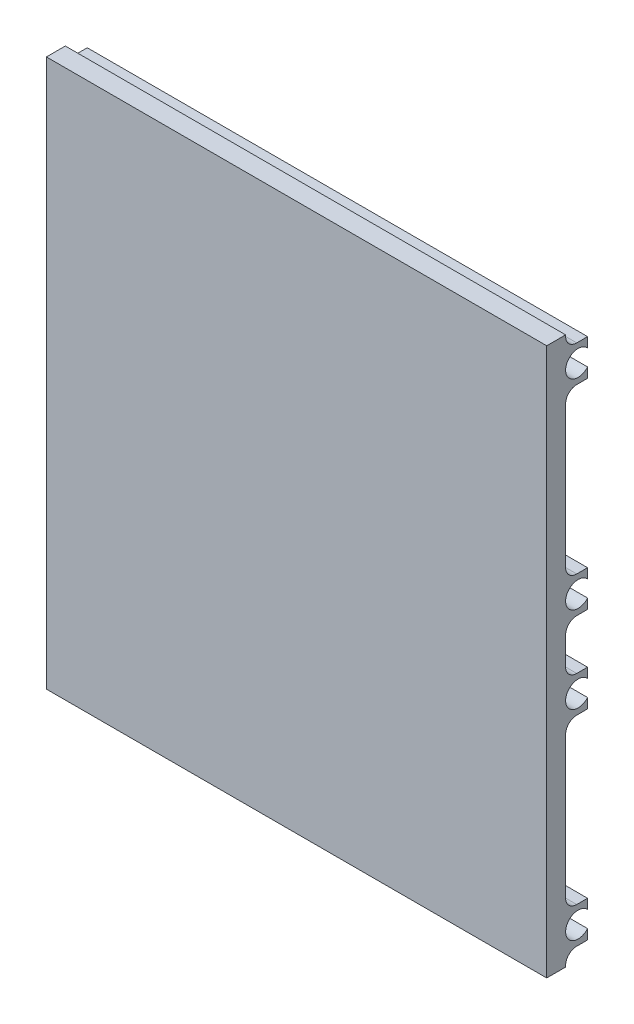
SolidWorks part; units mm, degrees
ref_plane "Спереди" through (0, 0, 0) normal (0, 0, 1) x (1, 0, 0)
ref_plane "Сверху" through (0, 0, 0) normal (0, 1, 0) x (1, 0, 0)
ref_plane "Справа" through (0, 0, 0) normal (1, 0, 0) x (0, 0, -1)
ref_plane "Плоскость4" through (90, 0, 0) normal (1, 0, 0) x (0, 0, -1)
sketch "Эскиз1" plane through (90, 0, 0) normal (1, 0, 0) x (0, 0, -1)
  line L0 (6.75, 225.9062) -> (6.75, 320.75)
  line L1 (6.75, 320.75) -> (-38.0938, 320.75)
  line L2 (-38.0938, 318.25) -> (-37.5, 318.25)
  line L3 (-37.5, 318.25) -> (-37.5, 284.75)
  line L4 (-37.5, 284.75) -> (-38.0938, 284.75)
  line L5 (-38.0938, 282.25) -> (-37.5, 282.25)
  line L6 (-37.5, 282.25) -> (-37.5, 269.25)
  line L7 (-37.5, 269.25) -> (-38.0938, 269.25)
  line L8 (-38.0938, 266.75) -> (-37.5, 266.75)
  line L9 (-37.5, 266.75) -> (-37.5, 233.25)
  line L10 (-37.5, 233.25) -> (-38.0938, 233.25)
  line L11 (-38.0938, 230.75) -> (-37.5, 230.75)
  line L12 (-37.5, 230.75) -> (-37.5, 226.5)
  line L13 (-37.5, 226.5) -> (-33.25, 226.5)
  line L14 (-33.25, 226.5) -> (-33.25, 225.9062)
  line L15 (-30.75, 225.9062) -> (-30.75, 226.5)
  line L16 (-30.75, 226.5) -> (-22.25, 226.5)
  line L17 (-22.25, 226.5) -> (-22.25, 225.9062)
  line L18 (-19.75, 225.9062) -> (-19.75, 226.5)
  line L19 (-19.75, 226.5) -> (-6.75, 226.5)
  line L20 (-6.75, 226.5) -> (-6.75, 225.9062)
  line L21 (-4.25, 225.9062) -> (-4.25, 226.5)
  line L22 (-4.25, 226.5) -> (4.25, 226.5)
  line L23 (4.25, 226.5) -> (4.25, 225.9062)
  arc A0 (-38.0938, 320.75) -> (-38.0938, 318.25) centre (-39.75, 319.5) ccw
  arc A1 (-38.0938, 284.75) -> (-38.0938, 282.25) centre (-39.75, 283.5) ccw
  arc A2 (-38.0938, 269.25) -> (-38.0938, 266.75) centre (-39.75, 268) ccw
  arc A3 (-38.0938, 233.25) -> (-38.0938, 230.75) centre (-39.75, 232) ccw
  arc A4 (-33.25, 225.9062) -> (-30.75, 225.9062) centre (-32, 224.25) ccw
  arc A5 (-22.25, 225.9062) -> (-19.75, 225.9062) centre (-21, 224.25) ccw
  arc A6 (-6.75, 225.9062) -> (-4.25, 225.9062) centre (-5.5, 224.25) ccw
  arc A7 (4.25, 225.9062) -> (6.75, 225.9062) centre (5.5, 224.25) ccw
extrude "Бобышка-Вытянуть1" add sketch "Эскиз1" against normal blind 90
sketch "Эскиз2" plane through (0, 320.75, 0) normal (0, 1, 0) x (-1, 0, 0)
  line L0 (-90, -6.75) -> (-90, 37.5)
  line L1 (-90, 37.5) -> (0, 37.5)
  line L2 (0, 37.5) -> (0, -6.75)
  line L3 (0, -6.75) -> (-90, -6.75)
extrude "Бобышка-Вытянуть2" add sketch "Эскиз2" along normal blind 8.2
sketch "Эскиз3" plane through (0, 0, -6.75) normal (0, 0, -1) x (-1, 0, 0)
  line L0 (-90, 226.5) -> (-90, 328.95)
  line L1 (-90, 328.95) -> (0, 328.95)
  line L2 (0, 328.95) -> (0, 226.5)
  line L3 (0, 226.5) -> (-90, 226.5)
extrude "Бобышка-Вытянуть3" add sketch "Эскиз3" along normal blind 8.2
sketch "Эскиз4" plane through (0, 0, 0) normal (-1, 0, 0) x (0, 0, 1)
  line L0 (24.25, 328.95) -> (24.25, 325)
  line L1 (24.25, 325) -> (28.75, 325)
  line L2 (28.75, 325) -> (28.75, 328.95)
  line L3 (28.75, 328.95) -> (24.25, 328.95)
extrude "Вырез-Вытянуть1" cut sketch "Эскиз4" against normal through all
sketch "Эскиз5" plane through (0, 0, 0) normal (-1, 0, 0) x (0, 0, 1)
  line L0 (37.5, 328.95) -> (35.25, 328.95)
  line L1 (35.25, 328.95) -> (35.25, 325)
  line L2 (35.25, 325) -> (37.5, 325)
  line L3 (37.5, 325) -> (37.5, 328.95)
extrude "Вырез-Вытянуть2" cut sketch "Эскиз5" against normal through all
sketch "Эскиз6" plane through (0, 0, 0) normal (-1, 0, 0) x (0, 0, 1)
  line L0 (-14.95, 226.5) -> (-11, 226.5)
  line L1 (-11, 226.5) -> (-11, 228.75)
  line L2 (-11, 228.75) -> (-14.95, 228.75)
  line L3 (-14.95, 228.75) -> (-14.95, 226.5)
extrude "Вырез-Вытянуть3" cut sketch "Эскиз6" against normal through all
sketch "Эскиз7" plane through (0, 0, 0) normal (-1, 0, 0) x (0, 0, 1)
  line L0 (-14.95, 235.25) -> (-11, 235.25)
  line L1 (-11, 235.25) -> (-11, 264.75)
  line L2 (-11, 264.75) -> (-14.95, 264.75)
  line L3 (-14.95, 264.75) -> (-14.95, 235.25)
extrude "Вырез-Вытянуть4" cut sketch "Эскиз7" against normal through all
sketch "Эскиз8" plane through (0, 0, 0) normal (-1, 0, 0) x (0, 0, 1)
  line L0 (-14.95, 271.25) -> (-11, 271.25)
  line L1 (-11, 271.25) -> (-11, 280.25)
  line L2 (-11, 280.25) -> (-14.95, 280.25)
  line L3 (-14.95, 280.25) -> (-14.95, 271.25)
extrude "Вырез-Вытянуть5" cut sketch "Эскиз8" against normal through all
sketch "Эскиз9" plane through (0, 0, 0) normal (-1, 0, 0) x (0, 0, 1)
  line L0 (-14.95, 286.75) -> (-11, 286.75)
  line L1 (-11, 286.75) -> (-11, 316.25)
  line L2 (-11, 316.25) -> (-14.95, 316.25)
  line L3 (-14.95, 316.25) -> (-14.95, 286.75)
extrude "Вырез-Вытянуть6" cut sketch "Эскиз9" against normal through all
sketch "Эскиз10" plane through (0, 0, 0) normal (-1, 0, 0) x (0, 0, 1)
  line L0 (-14.95, 328.95) -> (-14.95, 322.75)
  line L1 (-14.95, 322.75) -> (-11, 322.75)
  line L2 (-11, 322.75) -> (-11, 328.95)
  line L3 (-11, 328.95) -> (-14.95, 328.95)
extrude "Вырез-Вытянуть7" cut sketch "Эскиз10" against normal through all
sketch "Эскиз11" plane through (0, 0, 0) normal (-1, 0, 0) x (0, 0, 1)
  line L0 (-11, 328.95) -> (-11, 325)
  line L1 (-11, 325) -> (-8.75, 325)
  line L2 (-8.75, 325) -> (-8.75, 328.95)
  line L3 (-8.75, 328.95) -> (-11, 328.95)
extrude "Вырез-Вытянуть8" cut sketch "Эскиз11" against normal through all
sketch "Эскиз12" plane through (0, 0, 0) normal (-1, 0, 0) x (0, 0, 1)
  line L0 (-2.25, 328.95) -> (-2.25, 325)
  line L1 (-2.25, 325) -> (2.25, 325)
  line L2 (2.25, 325) -> (2.25, 328.95)
  line L3 (2.25, 328.95) -> (-2.25, 328.95)
extrude "Вырез-Вытянуть9" cut sketch "Эскиз12" against normal through all
sketch "Эскиз13" plane through (0, 0, 0) normal (-1, 0, 0) x (0, 0, 1)
  line L0 (8.75, 328.95) -> (8.75, 325)
  line L1 (8.75, 325) -> (17.75, 325)
  line L2 (17.75, 325) -> (17.75, 328.95)
  line L3 (17.75, 328.95) -> (8.75, 328.95)
extrude "Вырез-Вытянуть10" cut sketch "Эскиз13" against normal through all
sketch "Эскиз14" plane through (90, 0, 0) normal (1, 0, 0) x (0, 0, -1)
  line L0 (9.6, 323.6) -> (-36.1, 323.6)
  line L1 (-36.1, 323.6) -> (-36.1, 227.9)
  line L2 (-36.1, 227.9) -> (9.6, 227.9)
  line L3 (9.6, 227.9) -> (9.6, 323.6)
extrude "Вырез-Вытянуть11" cut sketch "Эскиз14" against normal blind 86
hole_wizard "Диаметр отверстия Ø2.5 (2.5)1" positions "Эскиз16" profile "Эскиз15" hole size "Ø2.5" standard "Ansi Metric"
sketch "Эскиз16" plane through (90, 0, 0) normal (1, 0, 0) x (0, 0, -1)
  point P0 (-39.75, 232)
  point P1 (-21, 224.25)
  point P2 (-39.75, 283.5)
  point P3 (-5.5, 224.25)
  point P4 (5.5, 224.25)
  point P5 (-39.75, 319.5)
  point P6 (-39.75, 268)
  point P7 (-32, 224.25)
sketch "Эскиз15" plane through (90, 232, 39.75) normal (0, 1, 0) x (0, 0, -1)
  line L0 (0, 0) -> (0, 90)
  line L1 (0, 90) -> (1.25, 90)
  line L2 (1.25, 90) -> (1.25, 0)
  line L5 (1.25, 0) -> (0, 0)
  line L11 (0, -6.35) -> (0, 107.95) construction
  dimension "Диаметр сквозного отверстия" = 2.5
  dimension "Глубина сквозного отверстия" = 90
hole_wizard "Диаметр отверстия Ø4.5 (4.5)1" positions "Эскиз18" profile "Эскиз17" hole size "Ø4.5" standard "Ansi Metric"
sketch "Эскиз18" plane through (0, 0, 0) normal (-1, 0, 0) x (0, 0, 1)
  point P0 (21, 327.25)
  point P1 (32, 327.25)
  point P2 (-13.25, 232)
  point P3 (-13.25, 268)
  point P4 (-13.25, 283.5)
  point P5 (-13.25, 319.5)
  point P6 (-5.5, 327.25)
  point P7 (5.5, 327.25)
sketch "Эскиз17" plane through (0, 327.25, 21) normal (0, 1, 0) x (0, 0, 1)
  line L0 (0, 0) -> (0, 90)
  line L1 (0, 90) -> (2.25, 90)
  line L2 (2.25, 90) -> (2.25, 0)
  line L5 (2.25, 0) -> (0, 0)
  line L11 (0, -6.35) -> (0, 107.95) construction
  dimension "Диаметр сквозного отверстия" = 4.5
  dimension "Глубина сквозного отверстия" = 90
hole_wizard "Диаметр отверстия Ø8.3 (8.3)1" positions "Эскиз20" profile "Эскиз19" hole size "Ø8.3" standard "Ansi Metric"
sketch "Эскиз20" plane through (0, 0, 0) normal (-1, 0, 0) x (0, 0, 1)
  point P0 (13.25, 275.75)
sketch "Эскиз19" plane through (0, 275.75, 13.25) normal (0, 1, 0) x (0, 0, 1)
  line L0 (0, 0) -> (0, 3.2)
  line L1 (0, 3.2) -> (4.15, 3.2)
  line L2 (4.15, 3.2) -> (4.15, 0)
  line L5 (4.15, 0) -> (0, 0)
  line L10 (0, 3.2) -> (-4.15, 3.2) construction
  line L11 (0, -6.35) -> (0, 107.95) construction
  dimension "Диаметр отверстия" = 8.3
  dimension "Глубина отверстия" = 3.2
  dimension "Угол заточки сверла" = 180
sketch "Эскиз21" plane through (0, 0, 0) normal (-1, 0, 0) x (0, 0, 1)
  circle A0 centre (13.25, 275.75) radius 4.15
extrude "Вырез-Вытянуть12" cut sketch "Эскиз21" against normal blind 10
sketch "Эскиз22" plane through (90, 0, 0) normal (1, 0, 0) x (0, 0, -1)
  circle A0 centre (-39.75, 319.5) radius 1.6316
  circle A1 centre (-39.75, 283.5) radius 1.5194
  circle A2 centre (-39.75, 268) radius 1.4876
  circle A3 centre (-39.75, 232) radius 1.5817
  circle A4 centre (-32, 224.25) radius 1.4878
  circle A5 centre (-21, 224.25) radius 1.426
  circle A6 centre (-5.5, 224.25) radius 1.6281
  circle A7 centre (5.5, 224.25) radius 1.5237
extrude "Бобышка-Вытянуть4" add sketch "Эскиз22" against normal blind 90
fillet "Скругление1" radius 2 1 edges at (4, 275.75, -9.6)
fillet "Скругление2" radius 2 1 edges at (4, 275.75, 36.1)
fillet "Скругление3" radius 2 3 edges at (4, 323.6, 13.25) (4.5858, 323.6, -9.0142) (4.5858, 323.6, 35.5142)
fillet "Скругление4" radius 2 3 edges at (4.5858, 227.9, -9.0142) (4, 227.9, 13.25) (4.5858, 227.9, 35.5142)
fillet "Скругление5" radius 2 1 edges at (45, 325, 35.25)
fillet "Скругление6" radius 2 1 edges at (45, 325, 28.75)
fillet "Скругление7" radius 2 1 edges at (45, 325, 24.25)
fillet "Скругление8" radius 2 1 edges at (45, 325, 17.75)
fillet "Скругление9" radius 2 1 edges at (45, 325, 8.75)
fillet "Скругление10" radius 2 1 edges at (45, 325, 2.25)
fillet "Скругление11" radius 2 1 edges at (45, 325, -2.25)
fillet "Скругление12" radius 2 1 edges at (45, 325, -8.75)
fillet "Скругление13" radius 2 1 edges at (45, 322.75, -11)
fillet "Скругление14" radius 2 1 edges at (45, 316.25, -11)
fillet "Скругление15" radius 2 1 edges at (45, 286.75, -11)
fillet "Скругление16" radius 2 1 edges at (45, 280.25, -11)
fillet "Скругление17" radius 2 1 edges at (45, 271.25, -11)
fillet "Скругление18" radius 2 1 edges at (45, 264.75, -11)
fillet "Скругление19" radius 2 1 edges at (45, 235.25, -11)
fillet "Скругление20" radius 2 1 edges at (45, 228.75, -11)
sketch "Эскиз23" plane through (90, 0, 0) normal (1, 0, 0) x (0, 0, -1)
  line L0 (9.6, 227.9) -> (9.6, 323.6) construction
  line L1 (9.6, 227.9) -> (9.6, 323.6)
  line L2 (9.6, 323.6) -> (9.6, 337.5289)
  line L3 (9.6, 337.5289) -> (-52.2821, 337.5289)
  line L4 (-52.2821, 337.5289) -> (-52.2821, 216.9593)
  line L5 (-52.2821, 216.9593) -> (9.6, 216.9593)
  line L6 (9.6, 216.9593) -> (9.6, 227.9)
extrude "Вырез-Вытянуть13" cut sketch "Эскиз23" against normal blind 122
sketch "Эскиз24" plane through (90, 0, 0) normal (1, 0, 0) x (0, 0, -1)
  line L0 (9.6, 226.5) -> (9.6, 325.3637) construction
  line L1 (9.6, 325) -> (9.6, 325.3637)
  line L2 (10.75, 325) -> (9.6, 325)
  arc A0 (9.6, 325.3637) -> (10.75, 325) centre (10.75, 327) ccw construction
  arc A1 (9.6, 325.3637) -> (10.75, 325) centre (10.75, 327) ccw
extrude "Вырез-Вытянуть14" cut sketch "Эскиз24" against normal blind 122
sketch "Эскиз25" plane through (0, 0, -9.6) normal (0, 0, 1) x (1, 0, 0)
  line L4 (90, 226.5) -> (90, 325)
  line L5 (90, 325) -> (0, 325)
  line L6 (0, 325) -> (0, 226.5)
  line L7 (0, 226.5) -> (90, 226.5)
  line L8 (90, 226.5) -> (90, 325)
  line L9 (90, 325) -> (0, 325)
  line L10 (0, 325) -> (0, 226.5)
  line L11 (0, 226.5) -> (90, 226.5)
  dimension "D1" = 0
extrude "Бобышка-Вытянуть5" add sketch "Эскиз25" along normal blind 2
